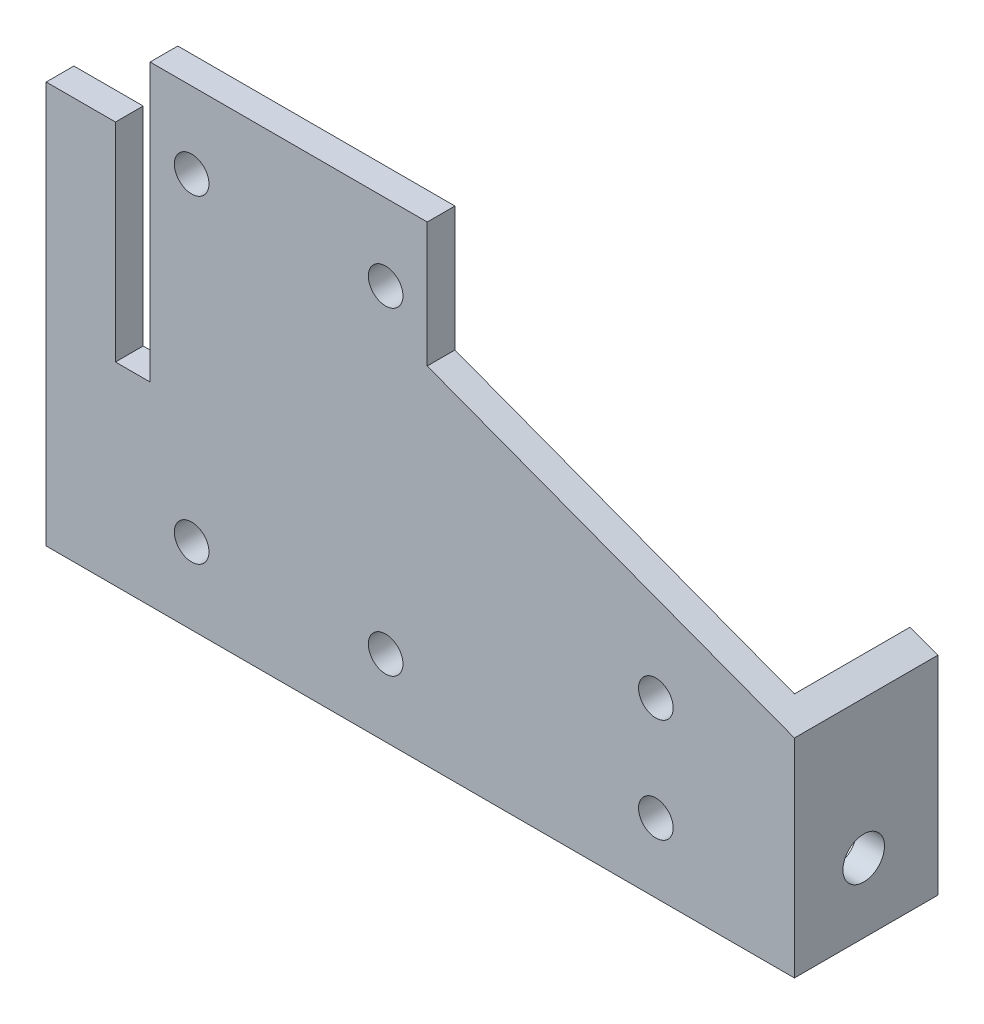
SolidWorks part; units mm, degrees
ref_plane "Спереди" through (0, 0, 0) normal (0, 0, 1) x (1, 0, 0)
ref_plane "Сверху" through (0, 0, 0) normal (0, 1, 0) x (1, 0, 0)
ref_plane "Справа" through (0, 0, 0) normal (1, 0, 0) x (0, 0, -1)
sketch "Эскиз1" plane through (0, 0, 0) normal (0, 0, 1) x (1, 0, 0)
  line L0 (35, 68) -> (35, 0) construction
  line L1 (0, 0) -> (108, 0)
  line L2 (0, 0) -> (0, 68)
  line L3 (0, 68) -> (55, 68)
  line L4 (108, 0) -> (108, 30)
  line L5 (21, 68) -> (21, 0) construction
  line L6 (55, 68) -> (55, 50)
  line L8 (49, 68) -> (49, 0) construction
  line L10 (108, 30) -> (55, 50)
  circle A0 centre (21, 57) radius 2.5
  circle A1 centre (49, 57) radius 2.5
  circle A2 centre (21, 11) radius 2.5
  circle A3 centre (49, 11) radius 2.5
  circle A4 centre (88, 10) radius 2.5
  circle A5 centre (88, 25) radius 2.5
  dimension "D8" = 5
  dimension "D9" = 5
  dimension "D10" = 5
  dimension "D11" = 5
  dimension "D18" = 5
  dimension "D20" = 5
  dimension "D1" = 108
  dimension "D2" = 68
  dimension "D3" = 55
  dimension "D4" = 30
  dimension "D5" = 35
  dimension "D6" = 14
  dimension "D7" = 14
  dimension "D12" = 46
  dimension "D13" = 46
  dimension "D14" = 11
  dimension "D15" = 11
  dimension "D16" = 20
  dimension "D17" = 10
  dimension "D19" = 20
  dimension "D21" = 15
extrude "Бобышка-Вытянуть1" add sketch "Эскиз1" along normal blind 4
sketch "Эскиз2" plane through (0, 0, 4) normal (0, 0, 1) x (1, 0, 0)
  line L1 (108, 0) -> (104, 0)
  line L2 (0, 0) -> (108, 0) construction
  line L3 (104, 0) -> (104, 31.5094)
  line L4 (108, 30) -> (55, 50) construction
  line L5 (104, 31.5094) -> (108, 30)
  line L6 (108, 30) -> (108, 0)
  dimension "D1" = 4
extrude "Бобышка-Вытянуть2" add sketch "Эскиз2" against normal blind 20.7
sketch "Эскиз3" plane through (108, 0, 0) normal (1, 0, 0) x (0, 0, -1)
  line L2 (-4, 0) -> (-4, 30) construction
  line L4 (-4, 0) -> (16.7, 0) construction
  circle A0 centre (6, 10) radius 3
  dimension "D1" = 6
  dimension "D2" = 10
  dimension "D3" = 10
extrude "Вырез-Вытянуть1" cut sketch "Эскиз3" against normal blind 6.7
sketch "Эскиз4" plane through (0, 0, 0) normal (0, 0, -1) x (-1, 0, 0)
  line L1 (0, 68) -> (-15, 68)
  line L2 (0, 68) -> (0, 58)
  line L3 (0, 58) -> (-10, 58)
  line L4 (-15, 68) -> (-15, 48)
  line L6 (-15, 48) -> (-15, 28)
  line L7 (-15, 28) -> (-10, 28)
  line L8 (-10, 58) -> (-10, 28)
  dimension "D1" = 10
  dimension "D2" = 10
  dimension "D3" = 40
  dimension "D4" = 5
extrude "Вырез-Вытянуть2" cut sketch "Эскиз4" against normal blind 10
